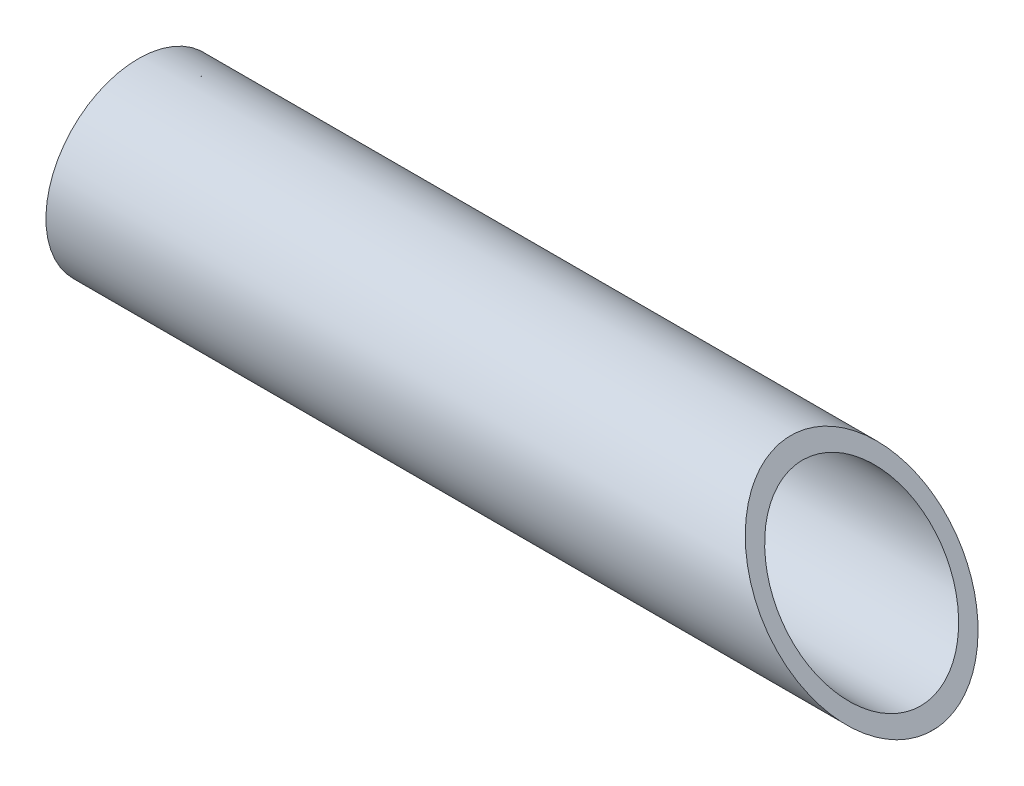
SolidWorks part; units mm, degrees
ref_plane "Front Plane" through (0, 0, 0) normal (0, 0, 1) x (1, 0, 0)
ref_plane "Top Plane" through (0, 0, 0) normal (0, 1, 0) x (1, 0, 0)
ref_plane "Right Plane" through (0, 0, 0) normal (1, 0, 0) x (0, 0, -1)
sketch "Sketch1" plane through (0, 0, 0) normal (1, 0, 0) x (0, 0, -1)
  circle A0 centre (0, 0) radius 30
  circle A1 centre (0, 0) radius 25
  dimension "D1" = 60
  dimension "D2" = 50
extrude "Boss-Extrude1" add sketch "Sketch1" along normal blind 258
sketch "Sketch2" plane through (0, 0, 0) normal (0, 0, 1) x (1, 0, 0)
  line L0 (0, 30) -> (212, 30) construction
  line L1 (258, 30) -> (0, 30) construction
  line L2 (212, 30) -> (266.8436, -41.4736)
  line L3 (212, 30) -> (269.8639, 30)
  line L4 (269.8639, 30) -> (266.8436, -41.4736)
  dimension "D1" = 212
  dimension "D2" = 127.5
extrude "Cut-Extrude1" cut sketch "Sketch2" against normal mid plane 258
